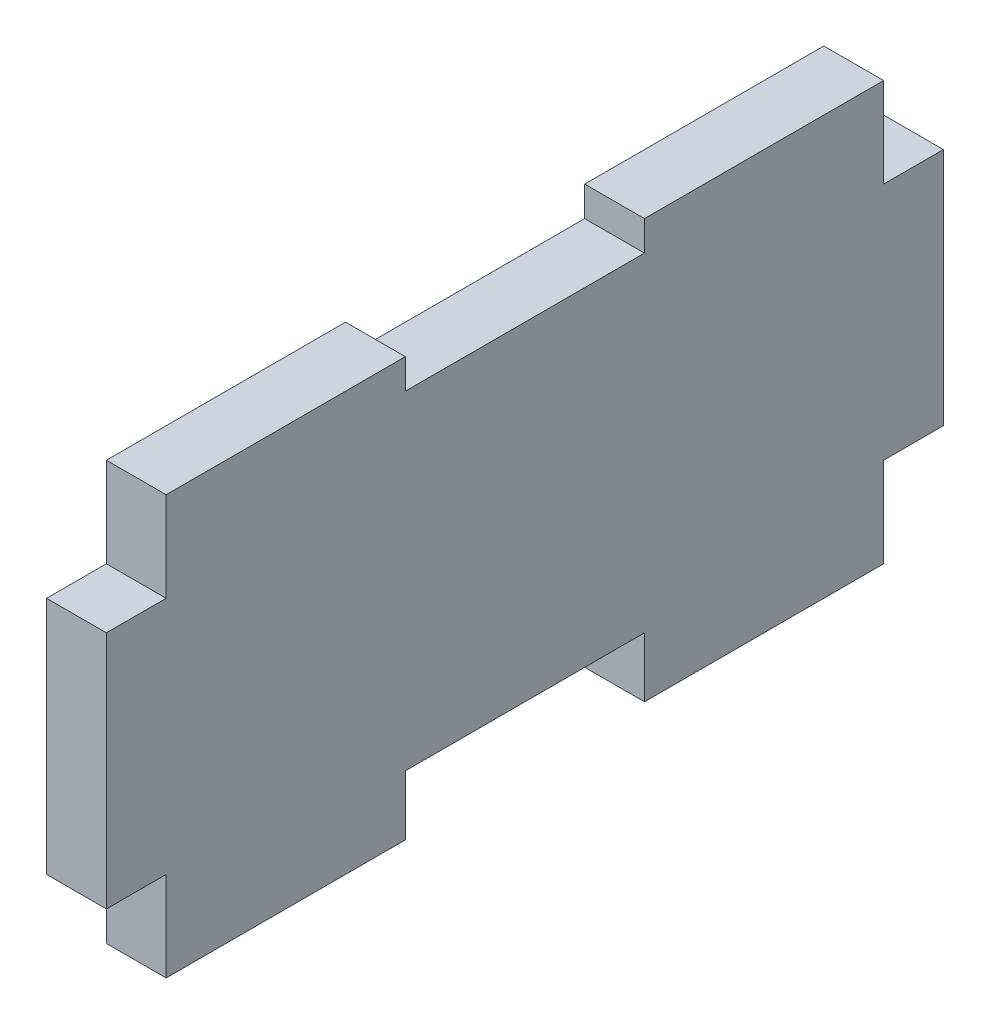
SolidWorks part; units mm, degrees
ref_plane "Front Plane" through (0, 0, 0) normal (0, 0, 1) x (1, 0, 0)
ref_plane "Top Plane" through (0, 0, 0) normal (0, 1, 0) x (1, 0, 0)
ref_plane "Right Plane" through (0, 0, 0) normal (1, 0, 0) x (0, 0, -1)
sketch "Sketch1" plane through (0, 0, 0) normal (1, 0, 0) x (0, 0, -1)
  line L1 (-140, 70) -> (0, 70)
  line L2 (-140, 70) -> (-140, 0)
  line L3 (-140, 0) -> (0, 0)
  line L4 (0, 70) -> (0, 0)
  line L5 (-140, 70) -> (-130, 70)
  line L6 (-140, 70) -> (-140, 55)
  line L7 (-140, 55) -> (-130, 55)
  line L8 (-130, 70) -> (-130, 55)
  line L9 (-140, 0) -> (-130, 0)
  line L10 (-140, 0) -> (-140, 15)
  line L11 (-140, 15) -> (-130, 15)
  line L12 (-130, 0) -> (-130, 15)
  line L13 (0, 70) -> (-10, 70)
  line L14 (0, 70) -> (0, 55)
  line L15 (0, 55) -> (-10, 55)
  line L16 (-10, 70) -> (-10, 55)
  line L17 (0, 0) -> (-10, 0)
  line L18 (0, 0) -> (0, 15)
  line L19 (0, 15) -> (-10, 15)
  line L20 (-10, 0) -> (-10, 15)
  line L21 (-90, 70) -> (-50, 70)
  line L22 (-90, 70) -> (-90, 65)
  line L23 (-90, 65) -> (-50, 65)
  line L24 (-50, 70) -> (-50, 65)
  line L25 (-90, 0) -> (-50, 0)
  line L26 (-90, 0) -> (-90, 10)
  line L27 (-90, 10) -> (-50, 10)
  line L28 (-50, 0) -> (-50, 10)
  dimension "D1" = 140
  dimension "D2" = 70
  dimension "D3" = 10
  dimension "D4" = 15
  dimension "D5" = 10
  dimension "D6" = 15
  dimension "D7" = 15
  dimension "D8" = 10
  dimension "D9" = 10
  dimension "D10" = 15
  dimension "D11" = 5
  dimension "D12" = 40
  dimension "D13" = 50
  dimension "D14" = 50
  dimension "D15" = 40
  dimension "D16" = 10
extrude "Boss-Extrude1" add sketch "Sketch1" along normal blind 10 contours L28 L3 L20 L19 L4 L15 L16 L1 L24 L23 L22 L8 L7 L2 L11 L12 L26 L27
equation "\"D1@Sketch1\"=120+10+10"
